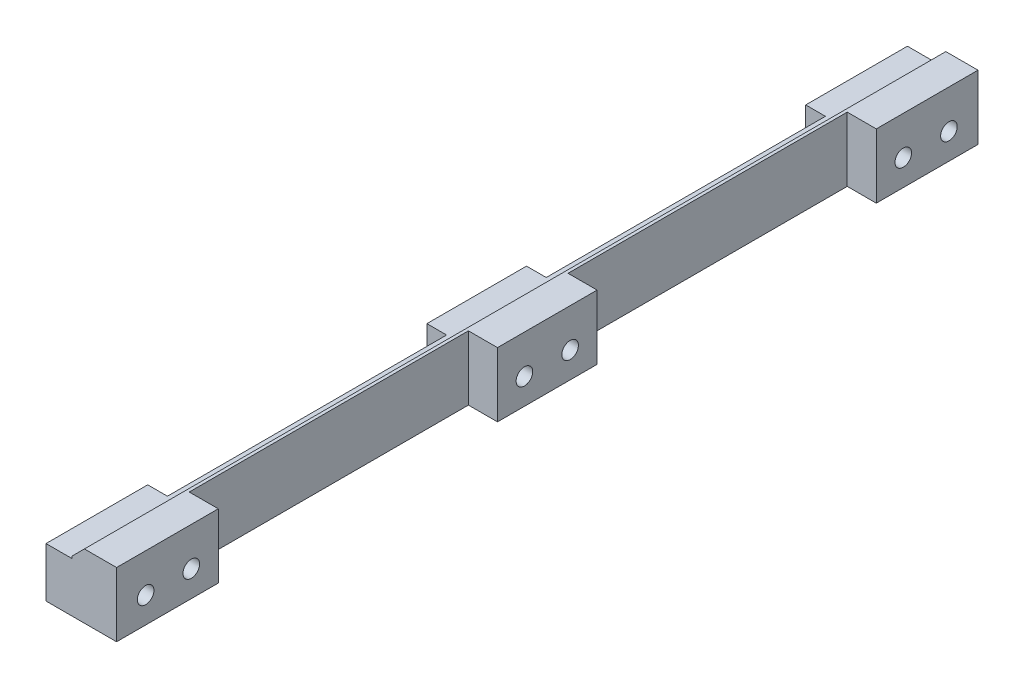
SolidWorks part; units mm, degrees
ref_plane "Front Plane" through (0, 0, 0) normal (0, 0, 1) x (1, 0, 0)
ref_plane "Top Plane" through (0, 0, 0) normal (0, 1, 0) x (1, 0, 0)
ref_plane "Right Plane" through (0, 0, 0) normal (1, 0, 0) x (0, 0, -1)
sketch "Sketch2" plane through (0, 0, 0) normal (0, 0, 1) x (1, 0, 0)
  line L0 (0, 0) -> (6.8, 0)
  line L1 (6.8, 0) -> (6.8, 6.2)
  line L2 (6.8, 6.2) -> (3.7, 6.2)
  line L3 (3.7, 6.2) -> (2.5, 5)
  line L4 (2.5, 5) -> (2.5, 4.8)
  line L5 (2.5, 4.8) -> (0, 4.8)
  line L6 (0, 4.8) -> (0, 0)
  point P10 (1.8208, 5.4234)
  dimension "D1" = 2.5
  dimension "D2" = 4.8
  dimension "D3" = 6.8
  dimension "D4" = 0.2
  dimension "D5" = 1.2
  dimension "D6" = 45
extrude "Boss-Extrude1" add sketch "Sketch2" along normal blind 9.8
sketch "Sketch3" plane through (0, 0, 9.8) normal (0, 0, 1) x (1, 0, 0)
  line L0 (0, 0) -> (0, 1.6)
  line L1 (0, 4.8) -> (0, 0) construction
  line L2 (0, 1.6) -> (1.9, 1.6)
  line L4 (2.5, 5) -> (3.7, 6.2)
  line L5 (3.7, 6.2) -> (4, 6.2)
  line L6 (6.8, 6.2) -> (3.7, 6.2) construction
  line L7 (4, 6.2) -> (4, 0)
  line L8 (0, 0) -> (6.8, 0) construction
  line L9 (4, 0) -> (0, 0)
  line L10 (2.5, 5) -> (2.5, 4.8)
  line L11 (2.5, 4.8) -> (1.9, 4.8)
  line L12 (2.5, 4.8) -> (0, 4.8) construction
  line L13 (1.9, 4.8) -> (1.9, 1.6)
  dimension "D1" = 4
  dimension "D2" = 1.6
  dimension "D3" = 0.6
extrude "Boss-Extrude2" add sketch "Sketch3" along normal blind 26.9
sketch "Sketch6" plane through (0, 0, 36.7) normal (0, 0, 1) x (1, 0, 0)
  line L0 (0, 0) -> (6.8, 0)
  line L1 (2.5, 4.8) -> (2.5, 5)
  line L2 (2.5, 5) -> (2.5, 4.8) construction
  line L3 (3.7, 6.2) -> (2.5, 5) construction
  line L4 (2.5, 5) -> (3.7, 6.2)
  line L5 (3.7, 6.2) -> (6.8, 6.2)
  line L6 (6.8, 6.2) -> (6.8, 0)
  line L7 (2.5, 4.8) -> (0, 4.8)
  line L8 (0, 4.8) -> (0, 0)
  dimension "D1" = 6.8
extrude "Boss-Extrude3" add sketch "Sketch6" along normal blind 9.6
sketch "Sketch7" plane through (0, 0, 46.3) normal (0, 0, 1) x (1, 0, 0)
  line L0 (0, 0) -> (0, 1.6)
  line L1 (0, 4.8) -> (0, 0) construction
  line L2 (2.5, 4.8) -> (2.5, 5)
  line L3 (2.5, 5) -> (3.7, 6.2)
  line L4 (3.7, 6.2) -> (4, 6.2)
  line L5 (6.8, 6.2) -> (3.7, 6.2) construction
  line L6 (4, 6.2) -> (4, 0)
  line L7 (0, 0) -> (6.8, 0) construction
  line L8 (4, 0) -> (0, 0)
  line L9 (2.5, 4.8) -> (1.9, 4.8)
  line L10 (2.5, 4.8) -> (0, 4.8) construction
  line L11 (1.9, 4.8) -> (1.9, 1.6)
  line L12 (1.9, 1.6) -> (0, 1.6)
  dimension "D1" = 1.6
  dimension "D2" = 4
  dimension "D3" = 0.6
extrude "Boss-Extrude4" add sketch "Sketch7" along normal blind 26.9
sketch "Sketch8" plane through (0, 0, 73.2) normal (0, 0, 1) x (1, 0, 0)
  line L0 (0, 0) -> (6.8, 0)
  line L1 (2.5, 4.8) -> (0, 4.8)
  line L2 (0, 4.8) -> (0, 0)
  line L3 (2.5, 4.8) -> (2.5, 5)
  line L4 (2.5, 5) -> (3.7, 6.2)
  line L5 (3.7, 6.2) -> (6.8, 6.2)
  line L6 (6.8, 6.2) -> (6.8, 0)
  dimension "D1" = 6.8
extrude "Boss-Extrude5" add sketch "Sketch8" along normal blind 9.8
hole_wizard "Tap Drill for M2x0.4 Tap1" positions "Sketch4" profile "Sketch5" hole size "M2x0.4" standard "ANSI Metric" end condition through all
sketch "Sketch4" plane through (0, 0, 0) normal (-1, 0, 0) x (0, 0, 1)
  line L0 (83, 0) -> (0, 0) construction
  line L1 (83, 0) -> (0, 0) construction
  line L2 (83, 0) -> (0, 0) construction
  point P0 (7.2, 2.5)
  point P2 (2.8, 2.5)
  point P8 (39.3, 2.5)
  point P10 (43.7, 2.5)
  point P16 (75.8, 2.5)
  point P18 (80.2, 2.5)
  point P20 (0, 0)
  point P21 (0, 0)
  dimension "D1" = 2.5
  dimension "D2" = 2.5
  dimension "D3" = 2.8
  dimension "D4" = 7.2
  dimension "D5" = 2.5
  dimension "D6" = 2.5
  dimension "D7" = 39.3
  dimension "D8" = 43.7
  dimension "D9" = 75.8
  dimension "D10" = 80.2
  dimension "D11" = 2.5
  dimension "D12" = 2.5
sketch "Sketch5" plane through (0, 2.5, 7.2) normal (0, 1, 0) x (0, 0, 1)
  line L0 (0, 0) -> (0, 6.8)
  line L1 (0, 6.8) -> (0.8, 6.8)
  line L2 (0.8, 6.8) -> (0.8, 0)
  line L5 (0.8, 0) -> (0, 0)
  line L11 (0, -6.35) -> (0, 107.95) construction
  dimension "Thru Hole Dia." = 1.6
  dimension "Thru Hole Depth" = 6.8
